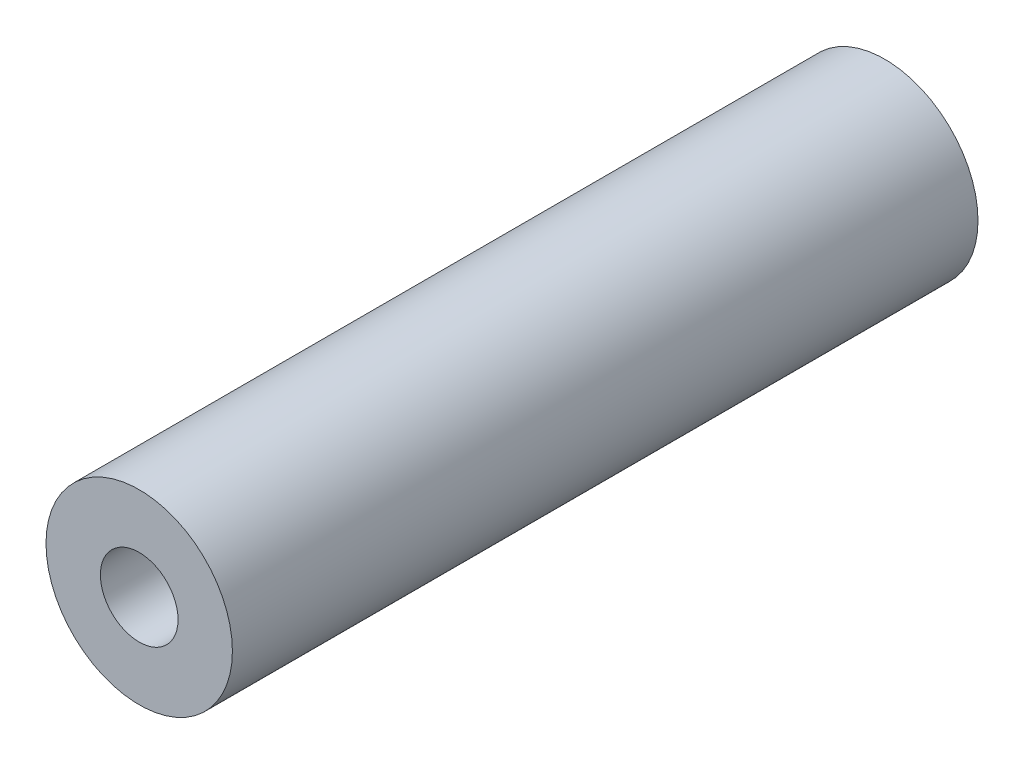
SolidWorks part; units mm, degrees
material "6063-T5"
ref_plane "正面" through (0, 0, 0) normal (0, 0, 1) x (1, 0, 0)
ref_plane "平面" through (0, 0, 0) normal (0, 1, 0) x (1, 0, 0)
ref_plane "右側面" through (0, 0, 0) normal (1, 0, 0) x (0, 0, -1)
sketch "ｽｹｯﾁ1" plane through (0, 0, 0) normal (0, 0, 1) x (1, 0, 0)
  circle A0 centre (0, 0) radius 3
  circle A1 centre (0, 0) radius 1.25
  dimension "D1" = 2.5
  dimension "D2" = 6
extrude "ﾎﾞｽ - 押し出し1" add sketch "ｽｹｯﾁ1" along normal blind 24
